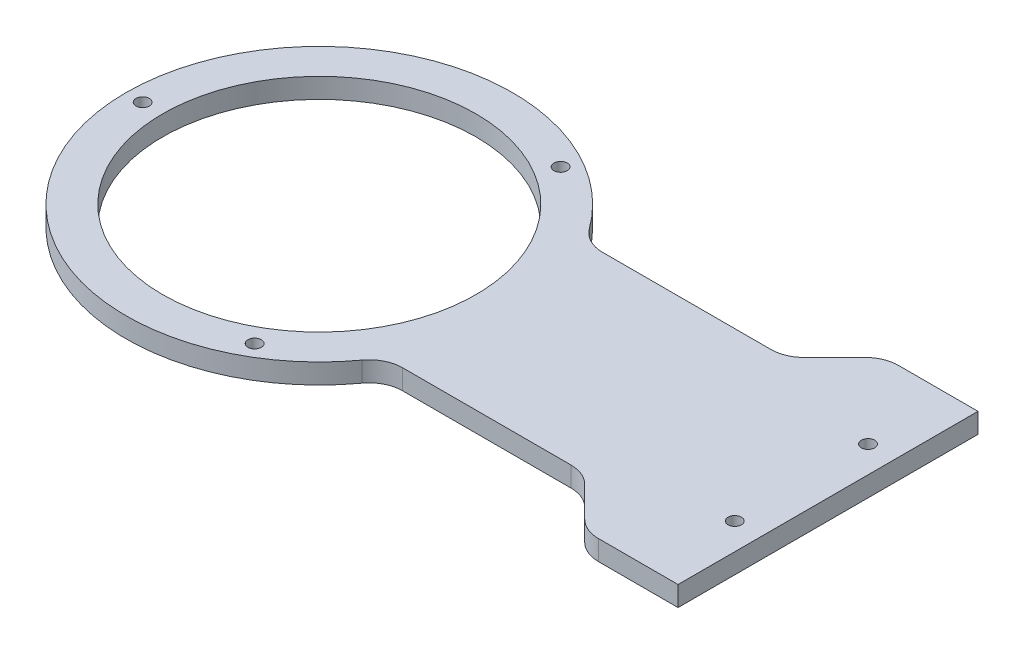
SolidWorks part; units mm, degrees
ref_plane "Front Plane" through (0, 0, 0) normal (0, 0, 1) x (1, 0, 0)
ref_plane "Top Plane" through (0, 0, 0) normal (0, 1, 0) x (1, 0, 0)
ref_plane "Right Plane" through (0, 0, 0) normal (1, 0, 0) x (0, 0, -1)
sketch "Sketch2" plane through (0, 0, 0) normal (0, 1, 0) x (1, 0, 0)
  line L0 (24.8193, 15) -> (54.8193, 15)
  line L1 (24.8193, -15) -> (54.8193, -15)
  line L2 (54.8193, 15) -> (62.3193, 22.5)
  line L3 (62.3193, 22.5) -> (76.3193, 22.5)
  line L4 (76.3193, 22.5) -> (76.3193, -22.5)
  line L5 (76.3193, -22.5) -> (62.3193, -22.5)
  line L6 (62.3193, -22.5) -> (54.8193, -15)
  line L7 (-55, 0) -> (55, 0) construction
  circle A0 centre (0, 0) radius 23 construction
  arc A1 (24.8193, 15) -> (24.8193, -15) centre (0, 0) ccw
  circle A2 centre (0, 0) radius 23.5
  circle A3 centre (72.3193, 10) radius 1
  circle A4 centre (72.3193, -10) radius 1
  point P13 (76.3193, 0)
  dimension "D1" = 46
  dimension "D3" = 58
  dimension "D12" = 2
  dimension "D2" = 0.5
  dimension "D4" = 30
  dimension "D5" = 30
  dimension "D6" = 45
  dimension "D7" = 14
  dimension "D8" = 45
  dimension "D9" = 45
  dimension "D10" = 4
  dimension "D11" = 10
extrude "Boss-Extrude1" add sketch "Sketch2" along normal blind 3 contours A1 L1 L6 L5 L4 L3 L2 L0 | A1 A2
fillet "Fillet1" radius 5 6 edges at (24.8193, 1.5, -15) (24.8193, 1.5, 15) (62.3193, 1.5, 22.5) (62.3193, 1.5, -22.5) (54.8193, 1.5, -15) (54.8193, 1.5, 15)
sketch "Sketch3" plane through (0, 3, 0) normal (0, 1, 0) x (1, 0, 0)
  line L0 (0, 0) -> (13.25, 22.9497) construction
  circle A0 centre (13.25, 22.9497) radius 1
  dimension "D3" = 2
  dimension "D1" = 26.5
  dimension "D2" = 60
extrude "Cut-Extrude1" cut sketch "Sketch3" against normal up to surface (3 mm away) up to face at (47.8673, 0, 0)
pattern_circular "CirPattern1" count 3 over 360 about axis through (0, 0, 0) along (0, 1, 0) of "Cut-Extrude1"
equation "\"motor-dia\" = 46"
equation "\"motor-holes-rad\" = 15"
equation "\"motor-height\" = 21"
equation "\"motor-case-thickness\" = 2"
equation "\"D1@Sketch2\"=\"motor-dia\""
